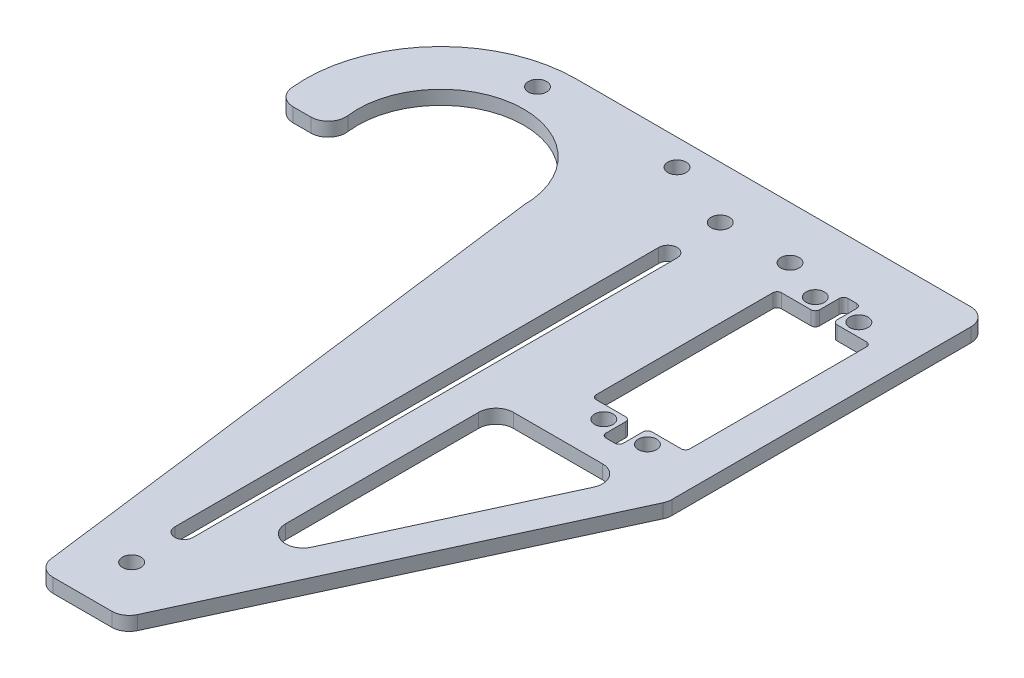
SolidWorks part; units mm, degrees
ref_plane "Front Plane" through (0, 0, 0) normal (0, 0, 1) x (1, 0, 0)
ref_plane "Top Plane" through (0, 0, 0) normal (0, 1, 0) x (1, 0, 0)
ref_plane "Right Plane" through (0, 0, 0) normal (1, 0, 0) x (0, 0, -1)
sketch "Sketch1" plane through (0, 0, 0) normal (0, 1, 0) x (1, 0, 0)
  line L0 (10, 79.5) -> (49.4809, 79.5)
  line L1 (10, -79.5) -> (-10, -79.5)
  line L2 (10, -79.5) -> (10, 6.0699) construction
  line L3 (10, 79.5) -> (-10, 79.5)
  line L4 (-10, -79.5) -> (-10, 79.5)
  line L5 (0, 79.5) -> (0, -79.5) construction
  line L6 (10, 0) -> (-10, 0) construction
  line L7 (49.4809, 79.5) -> (49.4809, 6.0699)
  line L8 (49.4809, 6.0699) -> (10, 6.0699) construction
  line L9 (25.7309, 63.5699) -> (35.7309, 63.5699) construction
  line L10 (30.7309, 15.0699) -> (30.7309, 63.5699) construction
  line L11 (19.9809, 60.5699) -> (28.7309, 60.5699)
  line L12 (19.9809, 60.5699) -> (19.9809, 18.0699)
  line L13 (19.9809, 18.0699) -> (28.7309, 18.0699)
  line L14 (41.4809, 60.5699) -> (41.4809, 18.0699)
  line L15 (25.7309, 15.0699) -> (35.7309, 15.0699) construction
  line L16 (28.7309, 60.5699) -> (28.7309, 67.0699)
  line L17 (28.7309, 67.0699) -> (32.7309, 67.0699)
  line L18 (32.7309, 67.0699) -> (32.7309, 60.5699)
  line L19 (28.7309, 18.0699) -> (28.7309, 11.5699)
  line L20 (28.7309, 11.5699) -> (32.7309, 11.5699)
  line L21 (32.7309, 11.5699) -> (32.7309, 18.0699)
  line L22 (32.7309, 60.5699) -> (41.4809, 60.5699)
  line L23 (32.7309, 18.0699) -> (41.4809, 18.0699)
  line L24 (0, 67.5) -> (16, 67.5) construction
  line L25 (0, -55.5) -> (0, 55.5) construction
  line L26 (-2.1, -55.5) -> (-2.1, 55.5)
  line L27 (2.1, -55.5) -> (2.1, 55.5)
  line L28 (-55.9834, 5.5957) -> (-91.6621, 5.9314) construction
  line L29 (-91.6621, 5.9314) -> (-65.0484, 21.2968) construction
  line L30 (-65.0484, 21.2968) -> (-55.9834, 5.5957) construction
  line L31 (0, 67.5) -> (0, 49.3699) construction
  line L32 (0, 49.3699) -> (30.7309, 49.3699) construction
  line L33 (30.7309, 49.3699) -> (0, 67.5) construction
  line L34 (49.4809, 6.0699) -> (10, -79.5)
  line L35 (10, -60.4044) -> (10, 6.0699)
  line L38 (40.6704, 6.0699) -> (10, -60.4044)
  line L40 (40.6704, 6.0699) -> (10, 6.0699)
  circle A0 centre (0, 67.5) radius 2.1
  circle A1 centre (0, -67.5) radius 2.1
  circle A2 centre (35.7309, 63.5699) radius 2.1
  circle A3 centre (25.7309, 63.5699) radius 2.1
  circle A4 centre (25.7309, 15.0699) radius 2.1
  circle A5 centre (35.7309, 15.0699) radius 2.1
  circle A6 centre (16, 67.5) radius 2.1
  arc A7 (-2.1, -55.5) -> (2.1, -55.5) centre (0, -55.5) ccw
  arc A8 (2.1, 55.5) -> (-2.1, 55.5) centre (0, 55.5) ccw
  circle A9 centre (30.7309, 49.3699) radius 7 construction
  point P0 (0, 0)
  point P19 (30.7309, 39.3199)
  point P20 (19.9809, 39.3199)
  point P22 (30.7309, 63.5699)
  point P25 (30.7309, 15.0699)
  point P40 (0, 0)
  dimension "D2" = 4.2
  dimension "D3" = 4.2
  dimension "D15" = 4.2
  dimension "D22" = 4.2
  dimension "D24" = 2.1
  dimension "D26" = 14
  dimension "D1" = 20
  dimension "D4" = 12
  dimension "D5" = 12
  dimension "D6" = 135
  dimension "D7" = 42.5
  dimension "D8" = 21.5
  dimension "D11" = 12
  dimension "D13" = 48.5
  dimension "D14" = 10
  dimension "D16" = 3
  dimension "D17" = 3
  dimension "D19" = 3
  dimension "D21" = 18.75
  dimension "D23" = 12
  dimension "D25" = 16
  dimension "D27" = 14.2
  dimension "D9" = 3.5
  dimension "D10" = 3.5
  dimension "D12" = 8
  dimension "D18" = 0
  dimension "D20" = 0
  dimension "D28" = 30.1301
  dimension "D29" = 18.75
extrude "Boss-Extrude1" add sketch "Sketch1" along normal blind 3.2
fillet "Fillet1" radius 4 8 edges at (-10, 1.6, 79.5) (49.4809, 1.6, -79.5) (-10, 1.6, -79.5) (10, 1.6, 60.4044) (40.6704, 1.6, -6.0699) (10, 1.6, -6.0699) (49.4809, 1.6, -6.0699) (10, 1.6, 79.5)
fillet "Fillet2" radius 1 12 edges at (19.9809, 1.6, -60.5699) (28.7309, 1.6, -60.5699) (28.7309, 1.6, -67.0699) (32.7309, 1.6, -60.5699) (32.7309, 1.6, -67.0699) (41.4809, 1.6, -60.5699) (41.4809, 1.6, -18.0699) (32.7309, 1.6, -18.0699) (19.9809, 1.6, -18.0699) (28.7309, 1.6, -18.0699) (28.7309, 1.6, -11.5699) (32.7309, 1.6, -11.5699)
sketch "Sketch2" plane through (0, 3.2, 0) normal (0, 1, 0) x (1, 0, 0)
  line L0 (-6, 79.5) -> (-45.05, 79.5)
  line L1 (-10, 75.5) -> (-10, -75.5) construction
  line L2 (-26, 48.45) -> (-62.787, 41.5) construction
  line L4 (-62.787, 41.5) -> (-75.3122, 41.5)
  line L7 (-26, 49.3726) -> (-26, 50049.3726) construction
  line L8 (-26, 48.45) -> (-10, -75.5)
  line L9 (-10, 75.5) -> (-10, -75.5)
  arc A0 (-26, 48.45) -> (-62.787, 41.5) centre (-45.05, 48.45) ccw
  arc A1 (-75.3122, 41.5) -> (-45.05, 79.5) centre (-45.05, 48.45) cw
  arc A3 (-10, 75.5) -> (-6, 79.5) centre (-6, 75.5) cw
  circle A4 centre (-47.9146, 73.5) radius 2.1
  circle A5 centre (-15.9146, 73.5) radius 2.1
  dimension "D2" = 12
  dimension "D3" = 19.05
  dimension "D6" = 4.2
  dimension "D1" = 16
  dimension "D4" = 38
  dimension "D5" = 32
  dimension "D7" = 6
extrude "Boss-Extrude2" add sketch "Sketch2" against normal blind 3.2
fillet "Fillet3" radius 4 2 edges at (-75.3122, 1.6, -41.5) (-62.787, 1.6, -41.5)
equation "\"screw\"= 4.2mm"
equation "\"D2@Sketch1\"=\"screw\""
equation "\"D3@Sketch1\"=\"screw\""
equation "\"dist\"= 12mm"
equation "\"D5@Sketch1\"=\"dist\""
equation "\"strength\"= 8mm"
equation "\"D11@Sketch1\"=\"strength\"+4"
equation "\"D15@Sketch1\"=\"screw\""
equation "\"D22@Sketch1\"=\"screw\""
